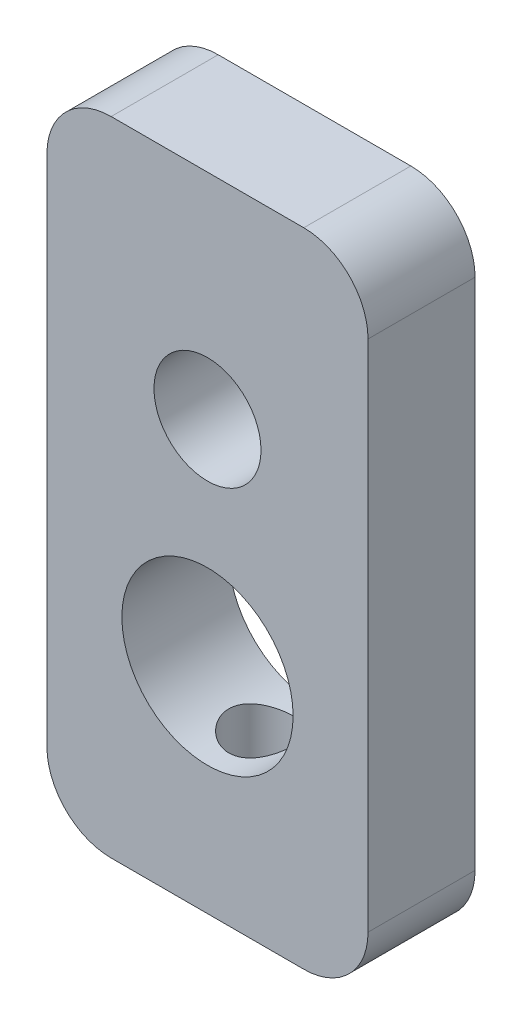
SolidWorks part; units mm, degrees
material "6061 Alloy"
ref_plane "Front Plane" through (0, 0, 0) normal (0, 0, 1) x (1, 0, 0)
ref_plane "Top Plane" through (0, 0, 0) normal (0, 1, 0) x (1, 0, 0)
ref_plane "Right Plane" through (0, 0, 0) normal (1, 0, 0) x (0, 0, -1)
sketch "Sketch1" plane through (0, 0, 0) normal (0, 0, 1) x (1, 0, 0)
  line L1 (-7.5, 20) -> (7.5, 20)
  line L2 (-7.5, 20) -> (-7.5, -10)
  line L3 (-7.5, -10) -> (7.5, -10)
  line L4 (7.5, 20) -> (7.5, -10)
  circle A1 centre (0, 0) radius 4
  dimension "D1" = 8
  dimension "D2" = 10
  dimension "D3" = 15
  dimension "D4" = 7.5
  dimension "D5" = 30
extrude "Boss-Extrude1" add sketch "Sketch1" along normal blind 5
sketch "Sketch2" plane through (0, -24.3792, 5) normal (0, 0, -1) x (1, 0, 0)
  line L0 (0, -27.1292) -> (0, -21.6292) construction
  circle A0 centre (0, -34.3792) radius 2.5
  circle A1 centre (0, -24.3792) radius 4 construction
  dimension "D1" = 5
  dimension "D2" = 10
sketch "Sketch3" plane through (0, 0, 0) normal (0, 1, 0) x (0, 0, -1)
  line L1 (0, 8.5759) -> (0, -8.5759) construction
  line L2 (-2.75, 0) -> (2.75, 0) construction
  circle A0 centre (-2.5, 0) radius 1.5
  dimension "D1" = 3
  dimension "D2" = 2.5
extrude "Cut-Extrude1" cut sketch "Sketch3" against normal blind 30
extrude "Cut-Extrude2" cut sketch "Sketch2" along normal blind 10
fillet "Fillet1" radius 3 4 edges at (7.5, -10, 2.5) (-7.5, -10, 2.5) (-7.5, 20, 2.5) (7.5, 20, 2.5)
